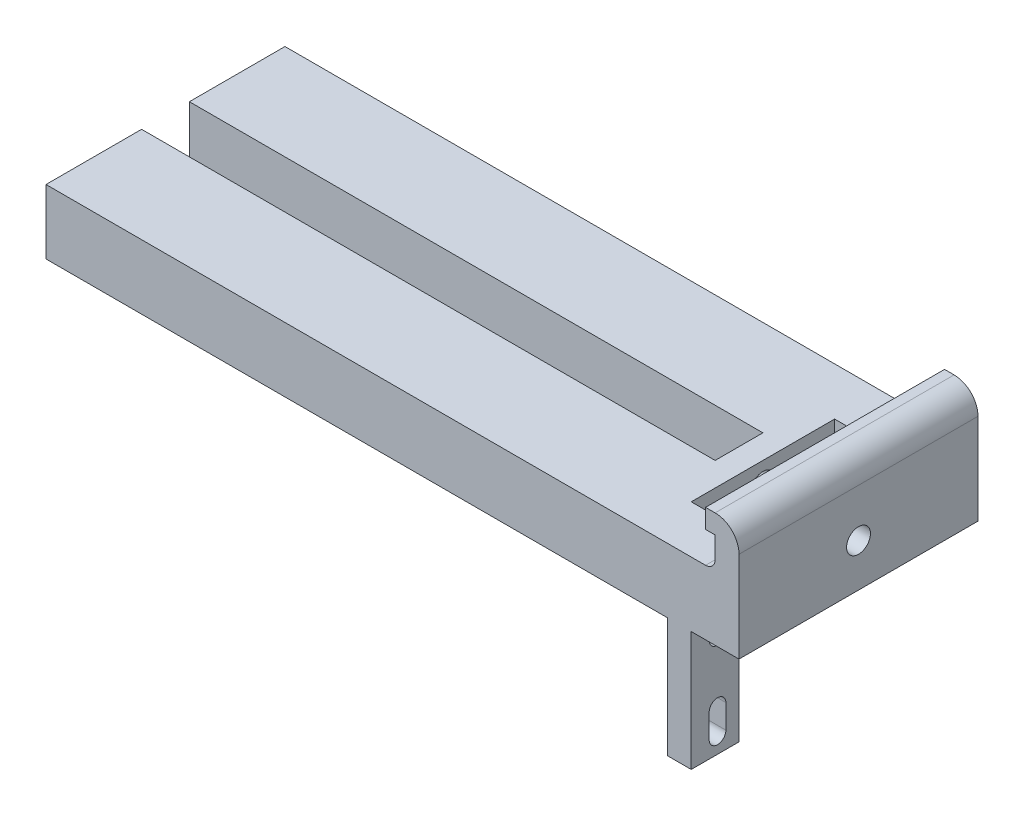
SolidWorks part; units mm, degrees
ref_plane "Front Plane" through (0, 0, 0) normal (0, 0, 1) x (1, 0, 0)
ref_plane "Top Plane" through (0, 0, 0) normal (0, 1, 0) x (1, 0, 0)
ref_plane "Right Plane" through (0, 0, 0) normal (1, 0, 0) x (0, 0, -1)
sketch "Sketch1" plane through (0, 0, 0) normal (0, 0, 1) x (1, 0, 0)
  line L0 (0, 0) -> (-140, 0)
  line L1 (-140, 0) -> (-140, 13.5)
  line L2 (-140, 13.5) -> (0, 13.5)
  line L3 (0, 13.5) -> (0, 0)
  dimension "D1" = 140
  dimension "D2" = 13.5
extrude "Boss-Extrude1" add sketch "Sketch1" along normal blind 50
sketch "Sketch2" plane through (-140, 0, 0) normal (-1, 0, 0) x (0, 0, 1)
  line L0 (50, 13.5) -> (50, 0) construction
  line L1 (12.5, 6.75) -> (25, 6.75) construction
  line L2 (25, 6.75) -> (37.5, 6.75) construction
  line L3 (37.5, 6.75) -> (50, 6.75) construction
  line L4 (0, 6.75) -> (12.5, 6.75) construction
  line L5 (0, 13.5) -> (0, 0) construction
  circle A0 centre (12.5, 6.75) radius 3
  circle A1 centre (25, 6.75) radius 3
  circle A2 centre (37.5, 6.75) radius 3
  point P9 (50, 6.75)
  dimension "D1" = 6
extrude "Cut-Extrude1" cut sketch "Sketch2" against normal blind 5
sketch "Sketch3" plane through (0, 0, 0) normal (1, 0, 0) x (0, 0, -1)
  line L0 (0, 0) -> (0, 24)
  line L1 (0, 0) -> (-50, 0)
  line L5 (-50, 0) -> (-50, 13.5) construction
  line L6 (-50, 0) -> (-50, 24)
  line L7 (-50, 24) -> (0, 24)
  dimension "D1" = 24
extrude "Boss-Extrude2" add sketch "Sketch3" along normal blind 5
sketch "Sketch4" plane through (0, 0, 0) normal (0, -1, 0) x (1, 0, 0)
  line L0 (5, 50) -> (5, 0) construction
  line L1 (-15, 40) -> (-5, 40)
  line L2 (-15, 40) -> (-15, 10)
  line L3 (-15, 10) -> (-5, 10)
  line L4 (-5, 40) -> (-5, 10)
  line L5 (-140, 0) -> (5, 0) construction
  line L7 (-140, 50) -> (5, 50) construction
  dimension "D1" = 10
  dimension "D2" = 10
  dimension "D3" = 10
  dimension "D4" = 10
extrude "Cut-Extrude2" cut sketch "Sketch4" against normal through all both and the other way through all
sketch "Sketch5" plane through (5, 0, 0) normal (1, 0, 0) x (0, 0, -1)
  line L0 (0, 0) -> (0, 24) construction
  line L1 (-50, 0) -> (0, 0) construction
  circle A0 centre (-25, 9) radius 2.5
  dimension "D3" = 5
  dimension "D1" = 25
  dimension "D2" = 9
extrude "Cut-Extrude3" cut sketch "Sketch5" against normal blind 35
sketch "Sketch6" plane through (0, 0, 0) normal (-1, 0, 0) x (0, 0, 1)
  line L0 (50, 24) -> (50, 13.5) construction
  line L1 (50, 20) -> (0, 20)
  line L2 (50, 20) -> (50, 24)
  line L3 (50, 24) -> (0, 24)
  line L4 (0, 20) -> (0, 24)
  line L5 (0, 13.5) -> (0, 24) construction
  line L6 (50, 13.5) -> (0, 13.5) construction
  dimension "D1" = 4
  dimension "D2" = 6.5
extrude "Boss-Extrude3" add sketch "Sketch6" along normal blind 2
sketch "Sketch7" plane through (0, 13.5, 0) normal (0, 1, 0) x (1, 0, 0)
  line L0 (-15, -40) -> (-15, -10) construction
  line L1 (-140, -20) -> (-20, -20)
  line L2 (-140, -20) -> (-140, -30)
  line L3 (-140, -30) -> (-20, -30)
  line L4 (-20, -20) -> (-20, -30)
  line L6 (-140, -50) -> (-140, 0) construction
  point P7 (-140, -25)
  point P10 (-140, -25)
  dimension "D1" = 5
  dimension "D2" = 10
extrude "Cut-Extrude4" cut sketch "Sketch7" against normal through all both and the other way through all
sketch "Sketch8" plane through (0, 0, 0) normal (0, -1, 0) x (1, 0, 0)
  line L0 (-140, 50) -> (5, 50) construction
  line L1 (-5, 40) -> (-10, 40)
  line L2 (-5, 40) -> (-5, 50)
  line L3 (-5, 50) -> (-10, 50)
  line L4 (-10, 40) -> (-10, 50)
  dimension "D1" = 5
extrude "Boss-Extrude4" add sketch "Sketch8" along normal blind 25
sketch "Sketch10" plane through (-10, 0, 0) normal (-1, 0, 0) x (0, 0, 1)
  line L0 (46.25, -16.5) -> (46.25, -21.5)
  line L3 (42.75, -21.5) -> (42.75, -16.5)
  line L4 (50, 0) -> (40, 0) construction
  line L5 (40, -25) -> (40, 0) construction
  circle A2 centre (44.5, -3.5) radius 1.75
  arc A3 (46.25, -16.5) -> (42.75, -16.5) centre (44.5, -16.5) ccw
  arc A4 (46.25, -21.5) -> (42.75, -21.5) centre (44.5, -21.5) cw
  point P16 (0, 0)
  dimension "D1" = 13
  dimension "D2" = 4.5
  dimension "D3" = 3.5
  dimension "D4" = 3.5
  dimension "D5" = 5
extrude "Cut-Extrude5" cut sketch "Sketch10" against normal through all both and the other way through all
fillet "Fillet1" radius 2 1 edges at (0, 13.5, 25)
fillet "Fillet2" radius 5 1 edges at (5, 24, 25)
